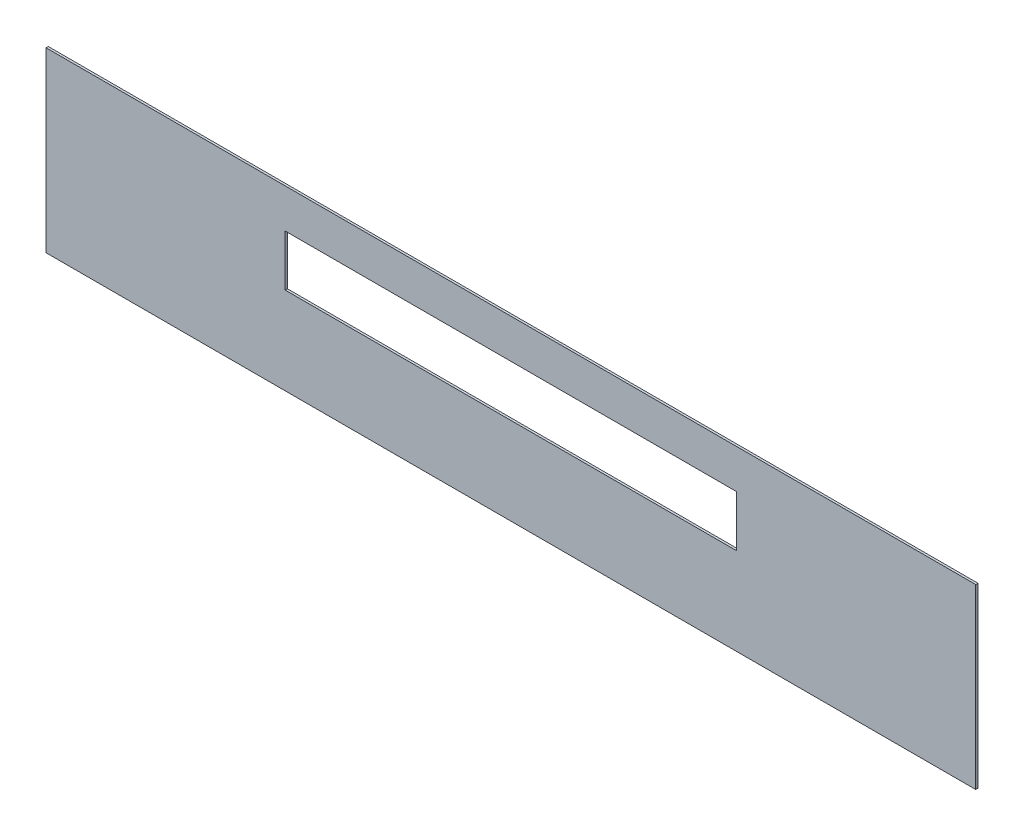
SolidWorks part; units mm, degrees
ref_plane "Front Plane" through (0, 0, 0) normal (0, 0, 1) x (1, 0, 0)
ref_plane "Top Plane" through (0, 0, 0) normal (0, 1, 0) x (1, 0, 0)
ref_plane "Right Plane" through (0, 0, 0) normal (1, 0, 0) x (0, 0, -1)
other "Configuration Table"
sketch "Sketch1" plane through (0, 0, 0) normal (0, 0, 1) x (1, 0, 0)
  line L1 (0, 0) -> (618, 0)
  line L2 (0, 0) -> (0, 118)
  line L3 (0, 118) -> (618, 118)
  line L4 (618, 0) -> (618, 118)
extrude "CEK_icecek_on_dis_sac_1.5_1" add sketch "Sketch1" along normal blind 1.5 from offset 38.5 separate body
sketch "Sketch2" plane through (0, 0, 0) normal (0, 0, 1) x (1, 0, 0)
  line L1 (159, 58) -> (459, 58)
  line L2 (159, 58) -> (159, 92)
  line L3 (159, 92) -> (459, 92)
  line L4 (459, 58) -> (459, 92)
extrude "CEK_icecek_on_dis_sac_1.5_2" cut sketch "Sketch2" along normal blind 14 from offset 27
